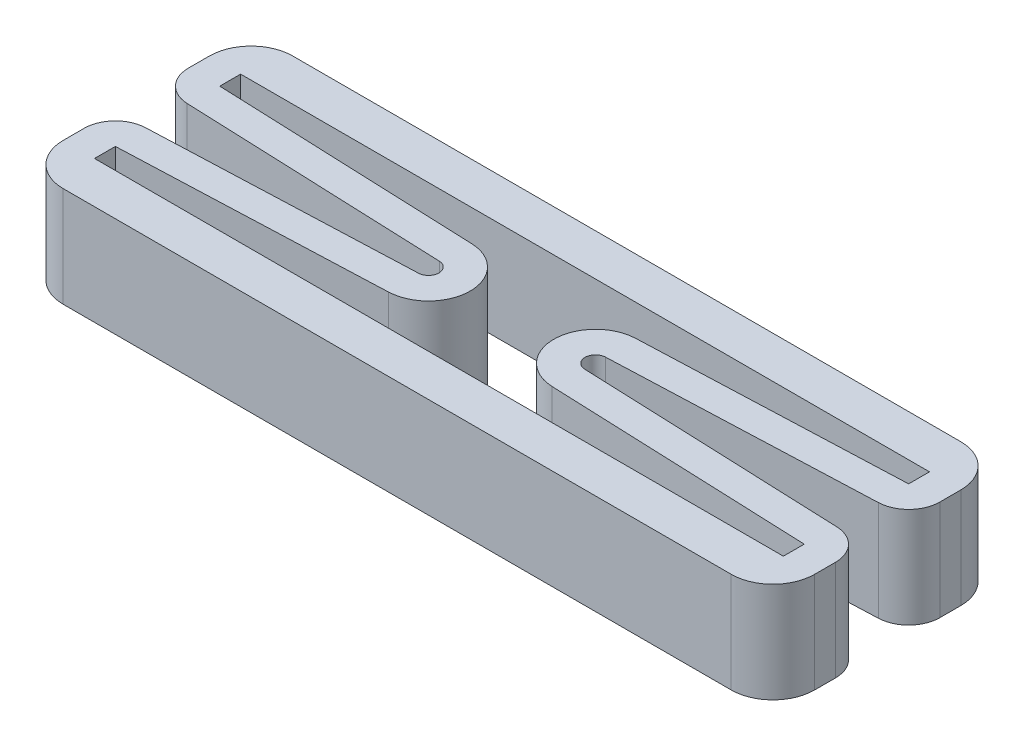
SolidWorks part; units mm, degrees
ref_plane "Front Plane" through (0, 0, 0) normal (0, 0, 1) x (1, 0, 0)
ref_plane "Top Plane" through (0, 0, 0) normal (0, 1, 0) x (1, 0, 0)
ref_plane "Right Plane" through (0, 0, 0) normal (1, 0, 0) x (0, 0, -1)
sketch "Sketch1" plane through (0, 0, 0) normal (0, 1, 0) x (1, 0, 0)
  line L0 (16.5, 3.5) -> (-16.5, 3.5)
  line L1 (16.5, 3.5) -> (18, 3.5) construction
  line L2 (16.5, 3.5) -> (16.5, 2.5)
  line L3 (16.5, 2.5) -> (18, 2.5) construction
  line L4 (18, 3.5) -> (18, 2.5)
  line L5 (16.5, 3.5) -> (18, 2.5) construction
  line L6 (16.5, 2.5) -> (18, 3.5) construction
  line L7 (-16, 5.5) -> (16, 5.5)
  line L8 (16.5, 2.5) -> (3.9203, 1.9984)
  line L9 (3.9801, 0.4996) -> (16.5598, 1.0012)
  line L10 (-9.9, 0) -> (9.9, 0) construction
  line L11 (-16, -5.5) -> (16, -5.5)
  line L12 (16.5, -3.5) -> (-16.5, -3.5)
  line L13 (16.5, -3.5) -> (16.5, -2.5)
  line L14 (18, -3.5) -> (18, -2.5)
  line L15 (16.5, -2.5) -> (3.9203, -1.9984)
  line L16 (3.9801, -0.4996) -> (16.5598, -1.0012)
  line L17 (0, -3.025) -> (0, 3.025) construction
  line L18 (-18, -3.5) -> (-18, -2.5)
  line L19 (-16.5, -3.5) -> (-16.5, -2.5)
  line L20 (-3.9801, -0.4996) -> (-16.5598, -1.0012)
  line L21 (-16.5, -2.5) -> (-3.9203, -1.9984)
  line L22 (-3.9801, 0.4996) -> (-16.5598, 1.0012)
  line L23 (-16.5, 2.5) -> (-3.9203, 1.9984)
  line L24 (-16.5, 3.5) -> (-16.5, 2.5)
  line L25 (-18, 3.5) -> (-18, 2.5)
  arc A0 (16, 5.5) -> (18, 3.5) centre (16, 3.5) cw
  arc A1 (3.9801, 0.4996) -> (3.9801, -0.4996) centre (4, 0) ccw
  arc A2 (3.9203, 1.9984) -> (3.9203, -1.9984) centre (4, 0) ccw
  arc A3 (16.5598, 1.0012) -> (18, 2.5) centre (16.5, 2.5) ccw
  arc A4 (16, -5.5) -> (18, -3.5) centre (16, -3.5) ccw
  arc A5 (16.5598, -1.0012) -> (18, -2.5) centre (16.5, -2.5) cw
  arc A6 (-16, -5.5) -> (-18, -3.5) centre (-16, -3.5) cw
  arc A7 (-16.5598, -1.0012) -> (-18, -2.5) centre (-16.5, -2.5) ccw
  arc A8 (-3.9801, 0.4996) -> (-3.9801, -0.4996) centre (-4, 0) cw
  arc A9 (-3.9203, 1.9984) -> (-3.9203, -1.9984) centre (-4, 0) cw
  arc A10 (-16.5598, 1.0012) -> (-18, 2.5) centre (-16.5, 2.5) cw
  arc A11 (-16, 5.5) -> (-18, 3.5) centre (-16, 3.5) ccw
  point P0 (17.25, 3)
  point P14 (0, 0)
  point P15 (0, 0)
  point P16 (0, 0)
  point P20 (0, 0)
  point P21 (0, 0)
  point P22 (0, 0)
  point P23 (0, 0)
  point P24 (16.9373, 2.5)
  point P25 (4.0044, 1.0357)
  point P26 (3.5, 2.1428)
  point P27 (0, 0)
  point P28 (3.1406, 2.2701)
  point P29 (0, 0)
  point P30 (3.6194, 2.1105)
  point P31 (3.8458, 0.7428)
  point P32 (4.0438, 0.8528)
  point P33 (4.7807, 2.2397)
  point P34 (4.0722, 2.0905)
  point P35 (4.1978, 0.6976)
  point P50 (0, -5.5)
  point P51 (0, -3.5)
  point P66 (0, 3.5)
  point P68 (0, 5.5)
  dimension "D7" = 2
  dimension "D1" = 1
  dimension "D2" = 1.5
  dimension "D3" = 16.5
  dimension "D4" = 2.5
  dimension "D5" = 2
  dimension "D6" = 4
extrude "Boss-Extrude1" add sketch "Sketch1" along normal blind 4.8
